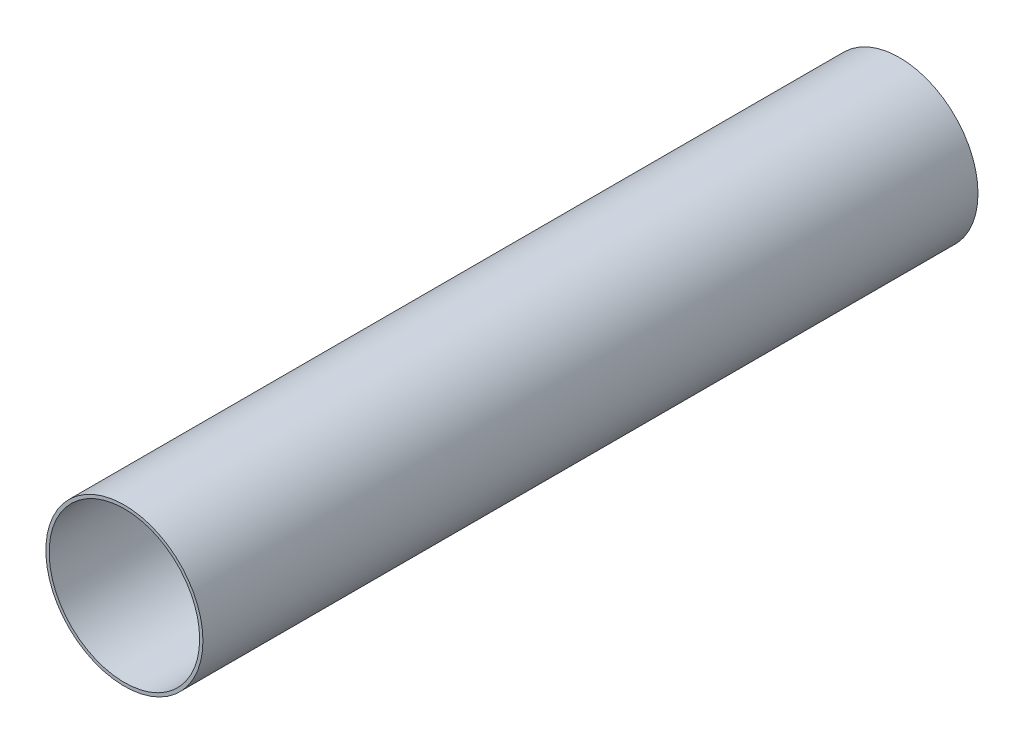
SolidWorks part; units mm, degrees
ref_plane "Front Plane" through (0, 0, 0) normal (0, 0, 1) x (1, 0, 0)
ref_plane "Top Plane" through (0, 0, 0) normal (0, 1, 0) x (1, 0, 0)
ref_plane "Right Plane" through (0, 0, 0) normal (1, 0, 0) x (0, 0, -1)
ref_plane "Plane1"
sketch "Sketch1" plane through (0, 0, 0) normal (0, 0, 1) x (1, 0, 0)
  circle A0 centre (0.1401, 0) radius 55
  circle A1 centre (0.1401, 0) radius 52.7
  dimension "D1" = 110
extrude "Extrusion1" add sketch "Sketch1" along normal blind 542.8 contours A0 A1
